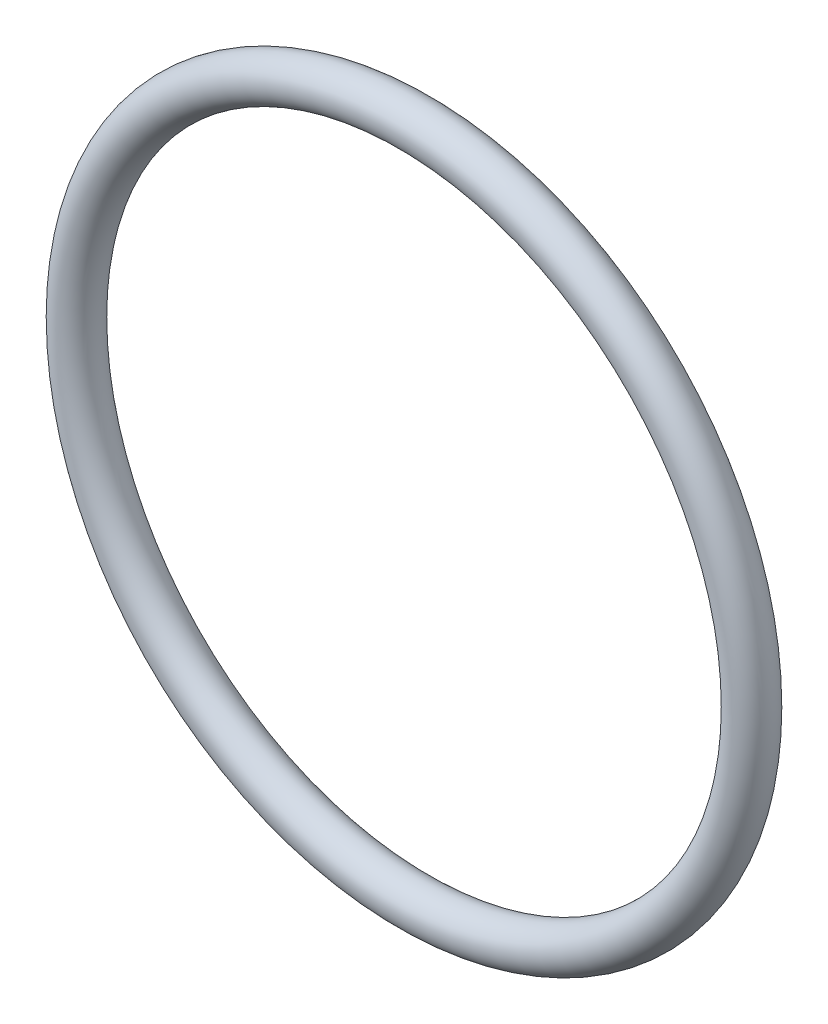
SolidWorks part; units mm, degrees
ref_plane "Front" through (0, 0, 0) normal (0, 0, 1) x (1, 0, 0)
ref_plane "Top" through (0, 0, 0) normal (0, 1, 0) x (1, 0, 0)
ref_plane "Right" through (0, 0, 0) normal (1, 0, 0) x (0, 0, -1)
sketch "Sketch1" plane through (0, 0, 0) normal (1, 0, 0) x (0, -1, 0)
  line L0 (0, -2.667) -> (0, 2.667) construction
  line L2 (-49.1744, 0) -> (49.1744, 0) construction
  line L3 (-39.37, 0) -> (39.37, 0) construction
  circle A0 centre (42.037, 0) radius 2.667
  point P9 (39.37, 0)
  point P10 (44.704, 0)
  point P13 (42.037, 2.667)
  point P14 (42.037, -2.667)
  dimension "Width" = 5.334
  dimension "ID" = 78.74
revolve "Revolve1" add sketch "Sketch1" angle 360 about L0
